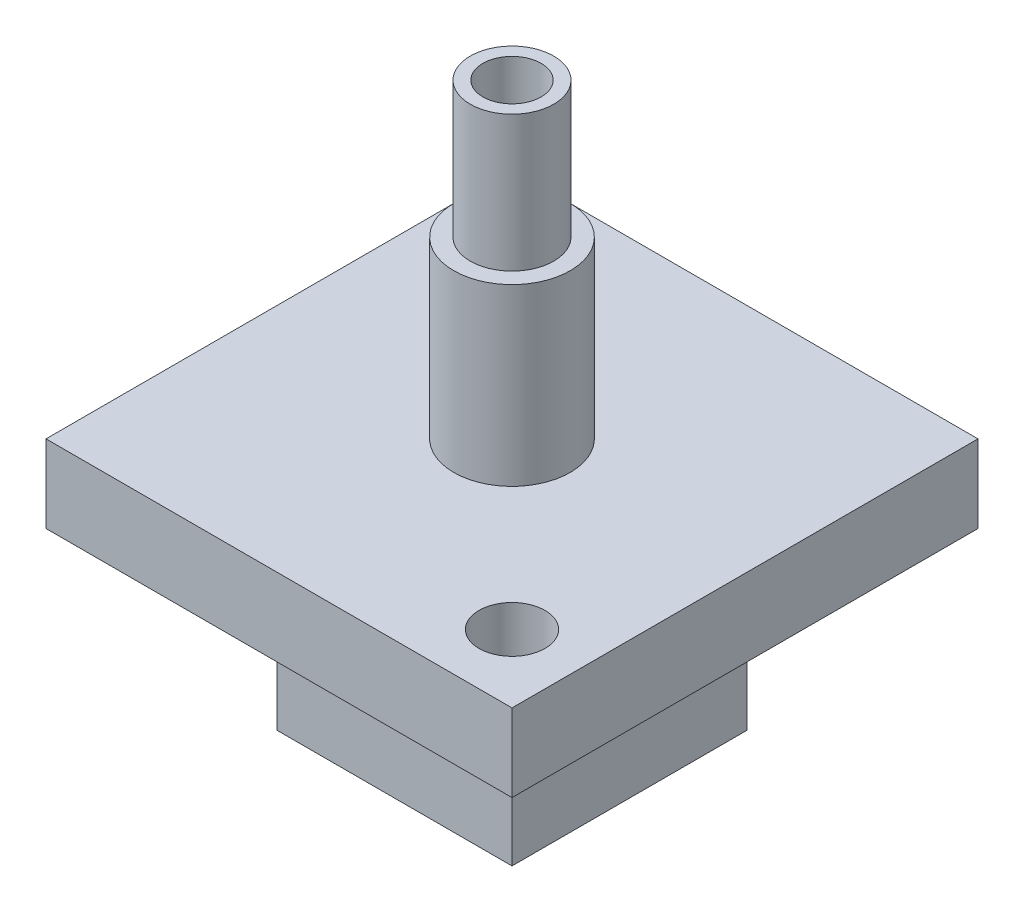
SolidWorks part; units mm, degrees
ref_plane "Front Plane" through (0, 0, 0) normal (0, 0, 1) x (1, 0, 0)
ref_plane "Top Plane" through (0, 0, 0) normal (0, 1, 0) x (1, 0, 0)
ref_plane "Right Plane" through (0, 0, 0) normal (1, 0, 0) x (0, 0, -1)
other "Configuration Table"
sketch "Sketch1" plane through (0, 0, 0) normal (0, 1, 0) x (1, 0, 0)
  line L0 (7.95, -6.05) -> (20.05, -6.05)
  line L1 (20.05, -6.05) -> (20.05, 6.05)
  line L2 (20.05, 6.05) -> (7.95, 6.05)
  line L3 (7.95, 6.05) -> (7.95, -6.05)
extrude "Spigot" add sketch "Sketch1" along normal blind 9 from offset 105
sketch "Sketch2" plane through (0, 0, 0) normal (0, 1, 0) x (1, 0, 0)
  line L0 (2, -12) -> (26, -12)
  line L1 (26, -12) -> (26, 12)
  line L2 (26, 12) -> (2, 12)
  line L3 (2, 12) -> (2, -12)
extrude "Flange" add sketch "Sketch2" along normal blind 4 from offset 114
sketch "Sketch3" plane through (0, 0, 0) normal (0, 1, 0) x (1, 0, 0)
  circle A0 centre (14, 0) radius 3
  dimension "D1" = 6
extrude "Outlet_Barb" add sketch "Sketch3" along normal blind 9 from offset 118
sketch "Sketch4" plane through (0, 0, 0) normal (0, 1, 0) x (1, 0, 0)
  circle A0 centre (14, 0) radius 2.15
  dimension "D1" = 4.3
extrude "Outlet_Barb_Tip" add sketch "Sketch4" along normal blind 7 from offset 127
sketch "Sketch5" plane through (0, 0, 0) normal (0, 1, 0) x (1, 0, 0)
  circle A0 centre (14, 0) radius 1.5
  dimension "D1" = 3
extrude "Outlet_Bore" cut sketch "Sketch5" against normal blind 29.2 from offset 134
sketch "Sketch6" plane through (0, 0, 0) normal (0, 1, 0) x (1, 0, 0)
  circle A0 centre (5.5, 8.5) radius 1.7
  circle A1 centre (22.5, -8.5) radius 1.7
  dimension "D1" = 3.4
  dimension "D2" = 3.4
extrude "Screw_Holes_M3" cut sketch "Sketch6" along normal blind 4.4 from offset 113.8
equation "\"Jar_OD\"= 90  'ASSUMED - Part G fallback - jar outer diameter"
equation "\"Jar_H\"= 120  'ASSUMED - Part G fallback - jar height"
equation "\"Pump_L\"= 45  'ASSUMED - Part G fallback"
equation "\"Pump_W\"= 24  'ASSUMED - Part G fallback"
equation "\"Pump_H\"= 33  'ASSUMED - Part G fallback"
equation "\"Pump_Outlet_OD\"= 7.5  'ASSUMED - Part G fallback"
equation "\"Tube_OD\"= 8  'ASSUMED - Part G fallback"
equation "\"Tube_ID\"= 6  'ASSUMED - Part G fallback"
equation "\"TDS_Body_Dia\"= 12  'ASSUMED - Part G fallback"
equation "\"TDS_Wet_Len\"= 45  'ASSUMED - Part G fallback - length in water"
equation "\"DS_Tube_Dia\"= 6  'ASSUMED - Part G fallback"
equation "\"DS_Tube_Len\"= 50  'ASSUMED - Part G fallback"
equation "\"ORP_Body_Dia\"= 12  'ASSUMED - Part G fallback"
equation "\"ORP_Body_Len\"= 150  'ASSUMED - Part G fallback"
equation "\"ORP_Cap_Dia\"= 16  'ASSUMED - Part G fallback"
equation "\"Turb_W\"= 33  'ASSUMED - Part G fallback - head width"
equation "\"Turb_D\"= 28  'ASSUMED - Part G fallback - head depth"
equation "\"Turb_H\"= 30  'ASSUMED - Part G fallback - head height"
equation "\"Turb_Slot_W\"= 10  'ASSUMED - Part G fallback - slot width"
equation "\"Flow_L\"= 62  'ASSUMED - Part G fallback YF-S201"
equation "\"Flow_W\"= 36  'ASSUMED - Part G fallback"
equation "\"Flow_H\"= 35  'ASSUMED - Part G fallback"
equation "\"Thread_G12_OD\"= 20.955  'ASSUMED - Part G fallback thread G1/2 (major diameter)"
equation "\"Valve_L\"= 75  'ASSUMED - Part G fallback"
equation "\"Valve_W\"= 45  'ASSUMED - Part G fallback"
equation "\"Valve_H\"= 60  'ASSUMED - Part G fallback"
equation "\"Tee_L\"= 40  'ASSUMED - Part G fallback - overall length"
equation "\"Tee_Branch_L\"= 25  'ASSUMED - Part G fallback"
equation "\"Tee_OD\"= 12  'ASSUMED - Part G fallback"
equation "\"LED_Board_L\"= 20  'ASSUMED - Part G fallback"
equation "\"LED_Board_W\"= 20  'ASSUMED - Part G fallback - LED at centre"
equation "\"GUVA_L\"= 20  'ASSUMED - Part G fallback"
equation "\"GUVA_W\"= 12  'ASSUMED - Part G fallback - sensor at centre"
equation "\"Reed_L\"= 27  'ASSUMED - Part G fallback MC-38 half"
equation "\"Reed_W\"= 14  'ASSUMED - Part G fallback"
equation "\"Reed_H\"= 8  'ASSUMED - Part G fallback"
equation "\"ESP_L\"= 51  'ASSUMED - Part G fallback"
equation "\"ESP_W\"= 28  'ASSUMED - Part G fallback"
equation "\"TFT_L\"= 58  'ASSUMED - Part G fallback - board"
equation "\"TFT_W\"= 35  'ASSUMED - Part G fallback - board"
equation "\"TFT_Win_L\"= 35  'ASSUMED - Part G fallback - visible window"
equation "\"TFT_Win_W\"= 28  'ASSUMED - Part G fallback - visible window"
equation "\"Relay_L\"= 50  'ASSUMED - Part G fallback"
equation "\"Relay_W\"= 26  'ASSUMED - Part G fallback"
equation "\"Relay_H\"= 19  'ASSUMED - Part G fallback"
equation "\"Mosfet_L\"= 34  'ASSUMED - Part G fallback"
equation "\"Mosfet_W\"= 17  'ASSUMED - Part G fallback"
equation "\"Mosfet_H\"= 12  'ASSUMED - Part G fallback"
equation "\"TDS_Board_L\"= 42  'ASSUMED - Part G fallback"
equation "\"TDS_Board_W\"= 32  'ASSUMED - Part G fallback"
equation "\"Turb_Board_L\"= 38  'ASSUMED - Part G fallback"
equation "\"Turb_Board_W\"= 28  'ASSUMED - Part G fallback"
equation "\"BNC_Thread_Dia\"= 9.5  'ASSUMED - Part G fallback"
equation "\"Plate_L\"= 420  'ASSUMED - Part G fallback"
equation "\"Plate_W\"= 297  'ASSUMED - Part G fallback"
equation "\"Plate_T\"= 6  'ASSUMED - Part G fallback"
equation "\"Booster_L\"= 150  'ASSUMED - Part G fallback - booster pump"
equation "\"Booster_W\"= 95  'ASSUMED - Part G fallback"
equation "\"Booster_H\"= 100  'ASSUMED - Part G fallback"
equation "\"PTube_OD\"= 6.35  'ASSUMED - Part G fallback - product tube 1/4 inch"
equation "\"Qz_Out\"= 12  'ASSUMED - Part G fallback - quartz channel outside square"
equation "\"Qz_Path\"= 10  'ASSUMED - Part G fallback - quartz channel inside light path"
equation "\"Qz_L\"= 40  'ASSUMED - Part G fallback - quartz channel length"
equation "\"LED860_Dia\"= 5  'ASSUMED - Part G fallback - 860 nm LED"
equation "\"BPW_L\"= 5.4  'ASSUMED - Part G fallback - BPW34"
equation "\"BPW_W\"= 4.3  'ASSUMED - Part G fallback - BPW34"
equation "\"Cart_Dia\"= 50  'ASSUMED - Part G fallback - sediment and pre-carbon cartridges"
equation "\"Cart_L\"= 255  'ASSUMED - Part G fallback"
equation "\"UF_Dia\"= 50  'ASSUMED - Part G fallback - UF cartridge"
equation "\"UF_L\"= 260  'ASSUMED - Part G fallback"
equation "\"RO_Dia\"= 62  'ASSUMED - Part G fallback - RO membrane housing"
equation "\"RO_L\"= 300  'ASSUMED - Part G fallback"
equation "\"UVC_Dia\"= 40  'ASSUMED - Part G fallback - UV-C chamber"
equation "\"UVC_L\"= 300  'ASSUMED - Part G fallback"
equation "\"Tank_W\"= 260  'ASSUMED - Part G fallback - storage tank"
equation "\"Tank_D\"= 160  'ASSUMED - Part G fallback"
equation "\"Tank_H\"= 300  'ASSUMED - Part G fallback"
equation "\"Cab_W\"= 400  'ASSUMED - Part G fallback - purifier cabinet"
equation "\"Cab_D\"= 270  'ASSUMED - Part G fallback"
equation "\"Cab_H\"= 560  'ASSUMED - Part G fallback"
equation "\"ORP_Board_L\"= 40  'ASSUMED - Part G fallback - ORP buffer board"
equation "\"ORP_Board_W\"= 30  'ASSUMED - Part G fallback"
equation "\"Opt_Board_L\"= 50  'ASSUMED - Part G fallback - optical front-end board"
equation "\"Opt_Board_W\"= 40  'ASSUMED - Part G fallback"
equation "\"Buck_L\"= 43  'ASSUMED - Part G fallback - 12 V to 5 V buck module"
equation "\"Buck_W\"= 21  'ASSUMED - Part G fallback"
equation "\"Buck_H\"= 14  'ASSUMED - Part G fallback"
equation "\"BB_L\"= 165  'ASSUMED - Part G fallback - breadboard (As_Built_R3 only)"
equation "\"BB_W\"= 55  'ASSUMED - Part G fallback"
equation "\"BB_H\"= 10  'ASSUMED - Part G fallback"
equation "\"Cuv_W\"= 12.5  'ASSUMED - old R3 cuvette (station suppressed in SS4)"
equation "\"Cuv_D\"= 12.5  'ASSUMED - old R3 cuvette (station suppressed in SS4)"
equation "\"Cuv_H\"= 45  'ASSUMED - old R3 cuvette (station suppressed in SS4)"
equation "\"Probe_Clr\"= 0.3  'DESIGN VALUE - Part C rule 3 - printed probe hole = diameter + 0.3"
equation "\"Label_H\"= 0.6  'DESIGN VALUE - Part D - raised label height"
equation "\"D1@Sketch3\" = \"Tube_ID\""
